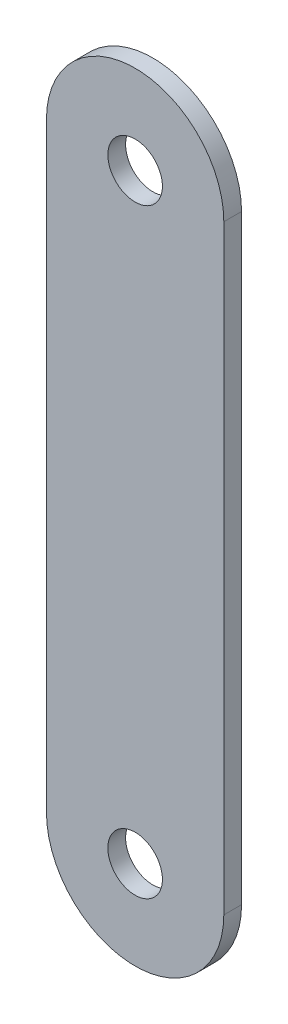
SolidWorks part; units mm, degrees
ref_plane "前视基准面" through (0, 0, 0) normal (0, 0, 1) x (1, 0, 0)
ref_plane "上视基准面" through (0, 0, 0) normal (0, 1, 0) x (1, 0, 0)
ref_plane "右视基准面" through (0, 0, 0) normal (1, 0, 0) x (0, 0, -1)
sketch "草图1" plane through (0, 0, 0) normal (0, 0, 1) x (1, 0, 0)
  line L0 (0, -22) -> (0, 22) construction
  line L1 (-6.5, -22) -> (-6.5, 22)
  line L2 (6.5, -22) -> (6.5, 22)
  arc A0 (-6.5, -22) -> (6.5, -22) centre (0, -22) ccw
  arc A1 (6.5, 22) -> (-6.5, 22) centre (0, 22) ccw
  circle A2 centre (0, 22) radius 2
  circle A3 centre (0, -22) radius 2
  point P2 (0, 0)
  dimension "D2" = 6.5
  dimension "D3" = 4
  dimension "D4" = 4
  dimension "D1" = 44
extrude "凸台-拉伸1" add sketch "草图1" along normal blind 1.3
